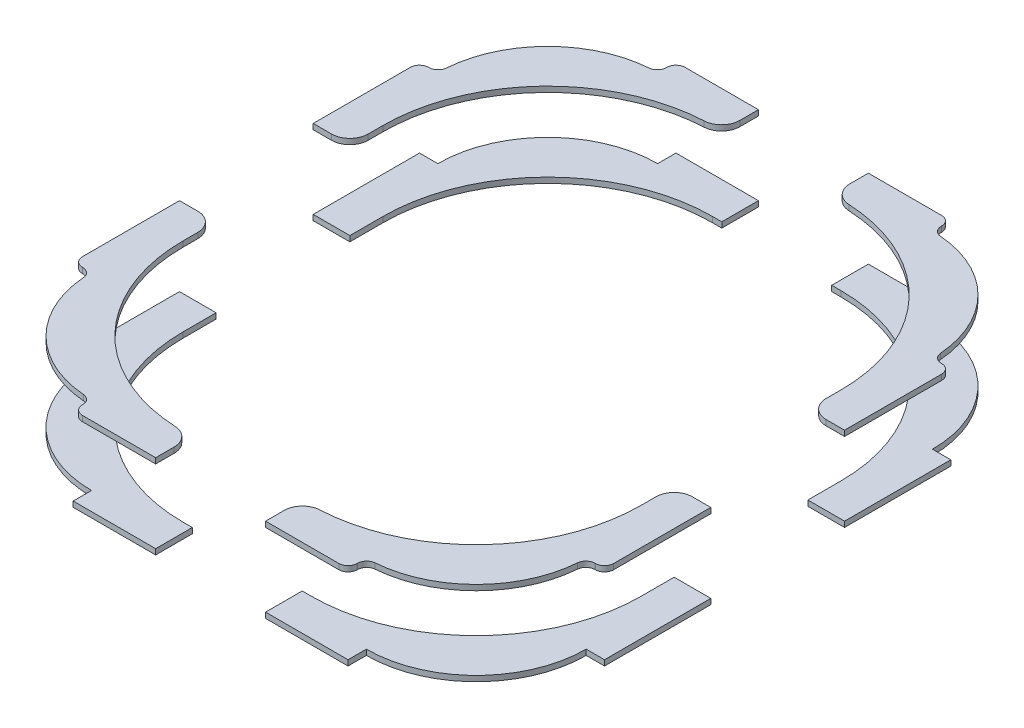
SolidWorks part; units mm, degrees
material "Alloy Steel"
ref_plane "Front Plane" through (0, 0, 0) normal (0, 0, 1) x (1, 0, 0)
ref_plane "Top Plane" through (0, 0, 0) normal (0, 1, 0) x (1, 0, 0)
ref_plane "Right Plane" through (0, 0, 0) normal (1, 0, 0) x (0, 0, -1)
sketch "Sketch1" plane through (0, 0, 0) normal (0, 1, 0) x (1, 0, 0)
  line L68 (0, 10) -> (0, -10)
  line L69 (0, -10) -> (-45, -10)
  line L70 (-115, 60) -> (-115, 118)
  line L71 (-115, 118) -> (-95, 118)
  line L74 (-105, 118) -> (-105, -94.3591) construction
  line L75 (0, 0) -> (-297.7724, 0) construction
  line L76 (-105, 60) -> (-115, 60)
  line L77 (-45, 0) -> (-45, -10)
  line L78 (-95, 118) -> (-95, 100)
  line L79 (0, 10) -> (-5, 10)
  line L80 (-231.8057, 154.5) -> (89.7646, 154.5) construction
  line L81 (0, 309) -> (-297.7724, 309) construction
  line L82 (-105, 191) -> (-105, 403.3591) construction
  line L83 (0, 299) -> (-5, 299)
  line L84 (-95, 191) -> (-95, 209)
  line L85 (-45, 309) -> (-45, 319)
  line L86 (-105, 249) -> (-115, 249)
  line L87 (-115, 191) -> (-95, 191)
  line L88 (-115, 249) -> (-115, 191)
  line L89 (0, 319) -> (-45, 319)
  line L90 (0, 299) -> (0, 319)
  line L91 (30, 456.0293) -> (30, -94.3591) construction
  line L92 (165, 191) -> (165, 403.3591) construction
  line L93 (60, 309) -> (357.7724, 309) construction
  line L94 (291.8057, 154.5) -> (-29.7646, 154.5) construction
  line L95 (60, 0) -> (357.7724, 0) construction
  line L96 (165, 118) -> (165, -94.3591) construction
  line L97 (60, 299) -> (60, 319)
  line L98 (60, 319) -> (105, 319)
  line L99 (175, 249) -> (175, 191)
  line L100 (175, 191) -> (155, 191)
  line L101 (165, 249) -> (175, 249)
  line L102 (105, 309) -> (105, 319)
  line L103 (155, 191) -> (155, 209)
  line L104 (60, 299) -> (65, 299)
  line L105 (60, 10) -> (65, 10)
  line L106 (155, 118) -> (155, 100)
  line L107 (105, 0) -> (105, -10)
  line L108 (165, 60) -> (175, 60)
  line L109 (175, 118) -> (155, 118)
  line L110 (175, 60) -> (175, 118)
  line L111 (60, -10) -> (105, -10)
  line L112 (60, 10) -> (60, -10)
  arc A25 (-105, 60) -> (-45, 0) centre (-45, 60) ccw
  arc A26 (-95, 100) -> (-5, 10) centre (-5, 100) ccw
  arc A27 (-95, 209) -> (-5, 299) centre (-5, 209) cw
  arc A28 (-105, 249) -> (-45, 309) centre (-45, 249) cw
  arc A29 (165, 249) -> (105, 309) centre (105, 249) ccw
  arc A30 (155, 209) -> (65, 299) centre (65, 209) ccw
  arc A31 (155, 100) -> (65, 10) centre (65, 100) cw
  arc A32 (165, 60) -> (105, 0) centre (105, 60) cw
  point P4 (0, 0)
  dimension "D5" = 115
  dimension "D6" = 128
  dimension "D7" = 36.5
  dimension "D8" = 30
  dimension "D1" = 20
  dimension "D3" = 90
  dimension "D4" = 60
  dimension "D2" = 20
extrude "Boss-Extrude1" add sketch "Sketch1" along normal blind 3
fillet "Fillet6" radius 10 2 edges at (60, 1.5, -10) (155, 1.5, -118)
fillet "Fillet7" radius 10 2 edges at (0, 1.5, -10) (-95, 1.5, -118)
fillet "Fillet8" radius 10 2 edges at (0, 1.5, -299) (-95, 1.5, -191)
fillet "Fillet9" radius 10 2 edges at (155, 1.5, -191) (60, 1.5, -299)
fillet "Fillet10" radius 5 4 edges at (-45, 1.5, -319) (-45, 1.5, -309) (-105, 1.5, -249) (-115, 1.5, -249)
fillet "Fillet11" radius 5 4 edges at (175, 1.5, -249) (165, 1.5, -249) (105, 1.5, -309) (105, 1.5, -319)
fillet "Fillet12" radius 5 4 edges at (105, 1.5, 10) (105, 1.5, 0) (165, 1.5, -60) (175, 1.5, -60)
fillet "Fillet13" radius 5 4 edges at (-115, 1.5, -60) (-105, 1.5, -60) (-45, 1.5, 0) (-45, 1.5, 10)
pattern_linear "LPattern1" count 2 spacing 43 along (0, -1, 0) of "Boss-Extrude1"
